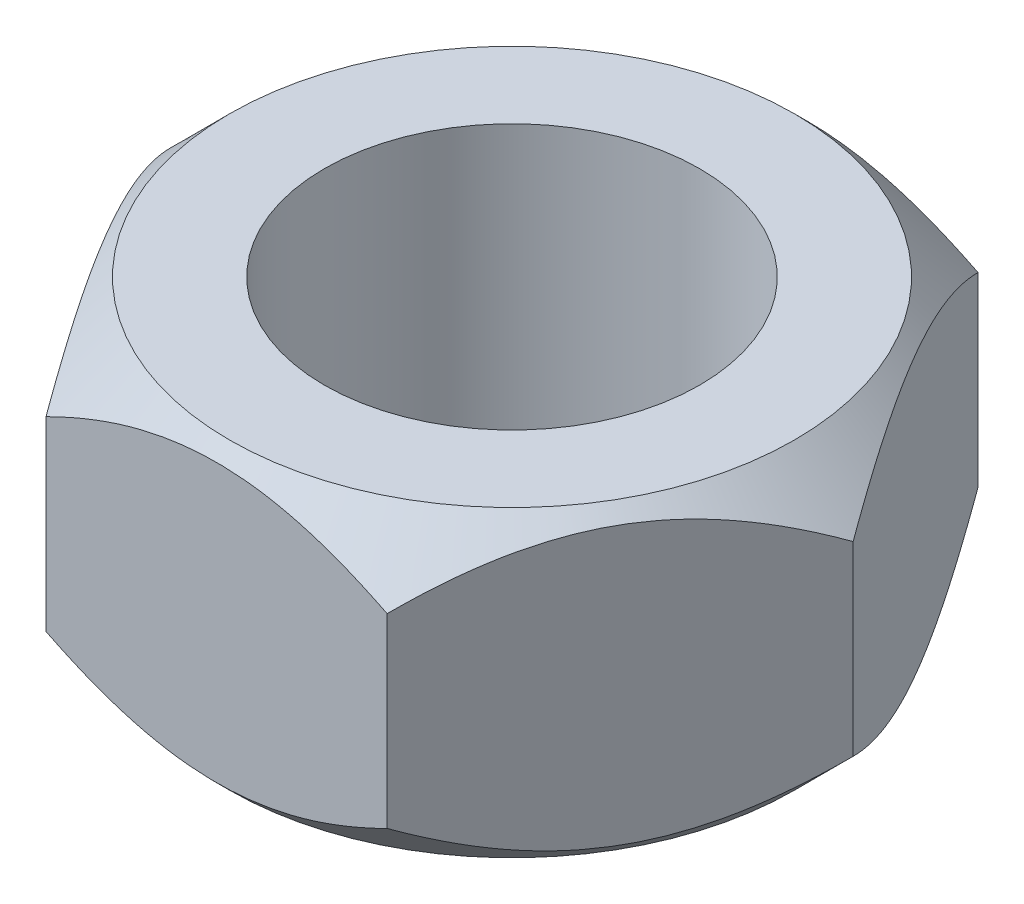
SolidWorks part; units mm, degrees
ref_plane "Front Plane" through (0, 0, 0) normal (0, 0, 1) x (1, 0, 0)
ref_plane "Top Plane" through (0, 0, 0) normal (0, 1, 0) x (1, 0, 0)
ref_plane "Right Plane" through (0, 0, 0) normal (1, 0, 0) x (0, 0, -1)
sketch "Sketch1" plane through (0, 0, 0) normal (0, 1, 0) x (1, 0, 0)
  line L1 (-10.9105, 0) -> (-5.4553, -9.4488)
  line L2 (-5.4553, -9.4488) -> (5.4553, -9.4488)
  line L3 (5.4553, -9.4488) -> (10.9105, 0)
  line L4 (10.9105, 0) -> (5.4553, 9.4488)
  line L5 (5.4553, 9.4488) -> (-5.4553, 9.4488)
  line L6 (-5.4553, 9.4488) -> (-10.9105, 0)
  circle A0 centre (0, 0) radius 9.4488 construction
  circle A1 centre (0, 0) radius 6
  dimension "D2" = 12
  dimension "D1" = 18.8976
extrude "Boss-Extrude1" add sketch "Sketch1" along normal blind 9.7 contours A1 | L1 L2 L3 L4 L5 L6
sketch "Sketch2" plane through (0, 0, 0) normal (1, 0, 0) x (0, 0, -1)
  line L5 (0, 0) -> (0, 12.4416) construction
sketch "Sketch3" plane through (0, 0, 0) normal (0, 0, 1) x (1, 0, 0)
  line L0 (-9.0355, 9.7) -> (-10.9105, 9.7)
  line L1 (-10.9105, 9.7) -> (-5.4553, 9.7) construction
  line L2 (-10.9105, 9.7) -> (-10.9105, 7.825)
  line L3 (-10.9105, 9.7) -> (-10.9105, 0) construction
  line L4 (-10.9105, 7.825) -> (-9.0355, 9.7)
  dimension "D1" = 1.875
  dimension "D2" = 1.875
revolve "Cut-Revolve3" cut sketch "Sketch3" angle 360 about L5
sketch "Sketch4" plane through (0, 0, 0) normal (0, 0, 1) x (1, 0, 0)
  line L0 (-9.0355, 0) -> (-10.9105, 0)
  line L1 (-10.9105, 0) -> (-5.4553, 0) construction
  line L2 (-10.9105, 0) -> (-10.9105, 1.875)
  line L3 (-10.9105, 7.825) -> (-10.9105, 0) construction
  line L4 (-10.9105, 1.875) -> (-9.0355, 0)
  dimension "D1" = 1.875
  dimension "D2" = 1.875
revolve "Cut-Revolve4" cut sketch "Sketch4" angle 360 about L5
